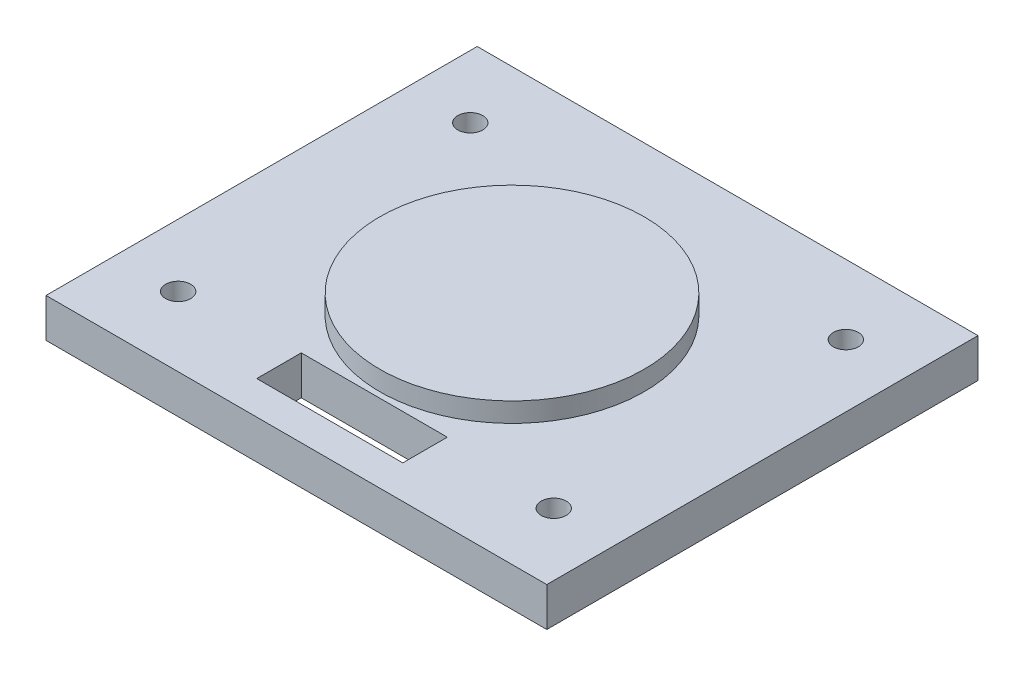
SolidWorks part; units mm, degrees
ref_plane "前视基准面" through (0, 0, 0) normal (0, 0, 1) x (1, 0, 0)
ref_plane "上视基准面" through (0, 0, 0) normal (0, 1, 0) x (1, 0, 0)
ref_plane "右视基准面" through (0, 0, 0) normal (1, 0, 0) x (0, 0, -1)
other "Configuration Table"
sketch "01_Base_Profile" plane through (0, 0, 0) normal (0, 1, 0) x (1, 0, 0)
  line L1 (-180, -155) -> (180, -155)
  line L2 (-180, -155) -> (-180, 155)
  line L3 (-180, 155) -> (180, 155)
  line L4 (180, -155) -> (180, 155)
  line L5 (-180, -155) -> (180, 155) construction
  line L6 (-180, 155) -> (180, -155) construction
  line L7 (-52.5, -131) -> (52.5, -131)
  line L8 (-52.5, -131) -> (-52.5, -99)
  line L9 (-52.5, -99) -> (52.5, -99)
  line L10 (52.5, -131) -> (52.5, -99)
  line L11 (-52.5, -131) -> (52.5, -99) construction
  line L12 (-52.5, -99) -> (52.5, -131) construction
  circle A0 centre (0, 0) radius 62.5
  circle A1 centre (-135, -105) radius 9
  circle A2 centre (135, -105) radius 9
  circle A3 centre (-135, 105) radius 9
  circle A4 centre (135, 105) radius 9
  point P0 (0, 0)
  point P16 (0, -115)
extrude "01_Base_Extrude" add sketch "01_Base_Profile" along normal blind 28
sketch "02_Boss_Profile" plane through (0, 0, 0) normal (0, 1, 0) x (1, 0, 0)
  circle A0 centre (0, 0) radius 95
extrude "02_Reinforcement_Boss" add sketch "02_Boss_Profile" along normal blind 42
